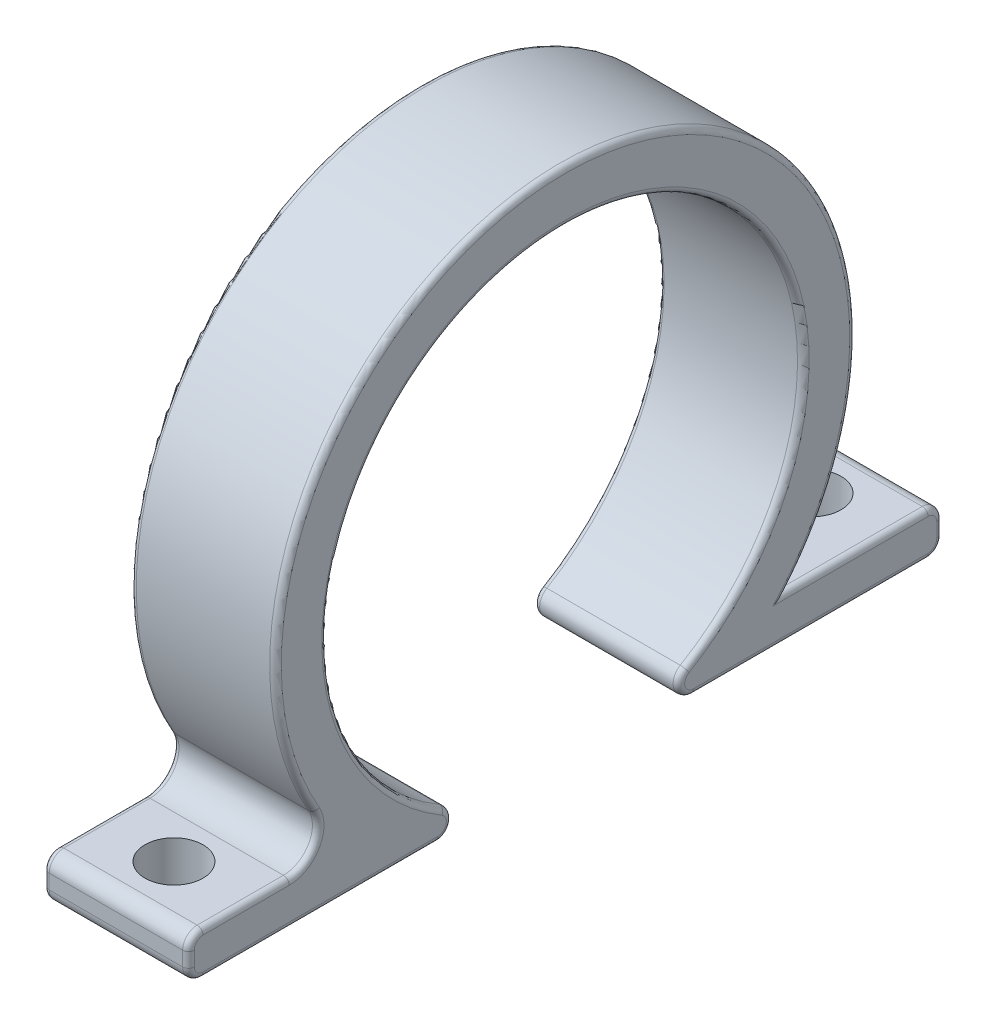
SolidWorks part; units mm, degrees
ref_plane "前视基准面" through (0, 0, 0) normal (0, 0, 1) x (1, 0, 0)
ref_plane "上视基准面" through (0, 0, 0) normal (0, 1, 0) x (1, 0, 0)
ref_plane "右视基准面" through (0, 0, 0) normal (1, 0, 0) x (0, 0, -1)
sketch "草图1" plane through (0, 0, 0) normal (1, 0, 0) x (0, 0, -1)
  line L0 (-12.5, -8) -> (-4.4091, -8)
  line L1 (-12.5, -6.5) -> (-9.5263, -6.5)
  line L2 (7.5993, -6.5) -> (12.5, -6.5)
  line L3 (4.4091, -8) -> (12.5, -8)
  line L4 (-13, -7) -> (-13, -7.5)
  line L5 (0, 0) -> (0, -15.4923) construction
  line L6 (13, -7) -> (13, -7.5)
  arc A0 (4.1557, -7.069) -> (-4.1557, -7.069) centre (0, 0) ccw
  arc A1 (7.5993, -6.5) -> (-8.6603, -5) centre (0, 0) ccw
  arc A2 (13, -7.5) -> (12.5, -8) centre (12.5, -7.5) cw
  arc A3 (13, -7) -> (12.5, -6.5) centre (12.5, -7) ccw
  arc A4 (-13, -7) -> (-12.5, -6.5) centre (-12.5, -7) cw
  arc A5 (-13, -7.5) -> (-12.5, -8) centre (-12.5, -7.5) ccw
  arc A6 (-8.6603, -5) -> (-9.5263, -6.5) centre (-9.5263, -5.5) cw
  arc A7 (4.4091, -8) -> (4.1557, -7.069) centre (4.4091, -7.5) cw
  arc A8 (-4.1557, -7.069) -> (-4.4091, -8) centre (-4.4091, -7.5) cw
  point P12 (13, -8)
  point P16 (13, -6.5)
  point P19 (-13, -6.5)
  point P22 (-13, -8)
  point P27 (1.8, -8)
  point P30 (0, 0)
  dimension "D1" = 8
  dimension "D2" = 1.5
  dimension "D3" = 0.5
  dimension "D4" = 1
  dimension "D5" = 0.5
extrude "凸台-拉伸1" add sketch "草图1" along normal blind 5
sketch "草图2" plane through (0, -6.5, 0) normal (0, 1, 0) x (1, 0, 0)
  circle A0 centre (2.5, -11) radius 1
  circle A1 centre (2.5, 11) radius 1
extrude "切除-拉伸1" cut sketch "草图2" against normal up to next
fillet "圆角1" radius 0.2 30 edges at (0, -7.25, -13) (0, -6.6464, -12.8536) (0, -6.5, -10.0497) (0, 9.9577, -0.9186) (0, -6, 8.6603) (0, -6.5, 11.0131) (0, -6.6464, 12.8536) (0, -7.25, 13) (0, -7.8536, 12.8536) (0, -8, 8.4545) (0, -7.6313, 3.9266) (0, 8.2, 0) (0, -7.6313, -3.9266) (0, -8, -8.4545) (0, -7.8536, -12.8536) (5, -8, -8.4545) (5, -7.6313, -3.9266) (5, 8.2, 0) (5, -7.6313, 3.9266) (5, -8, 8.4545) (5, -7.8536, 12.8536) (5, -7.25, 13) (5, -6.6464, 12.8536) (5, -6.5, 11.0131) (5, -6, 8.6603) (5, 9.9577, -0.9186) (5, -6.5, -10.0497) (5, -6.6464, -12.8536) (5, -7.25, -13) (5, -7.8536, -12.8536)
